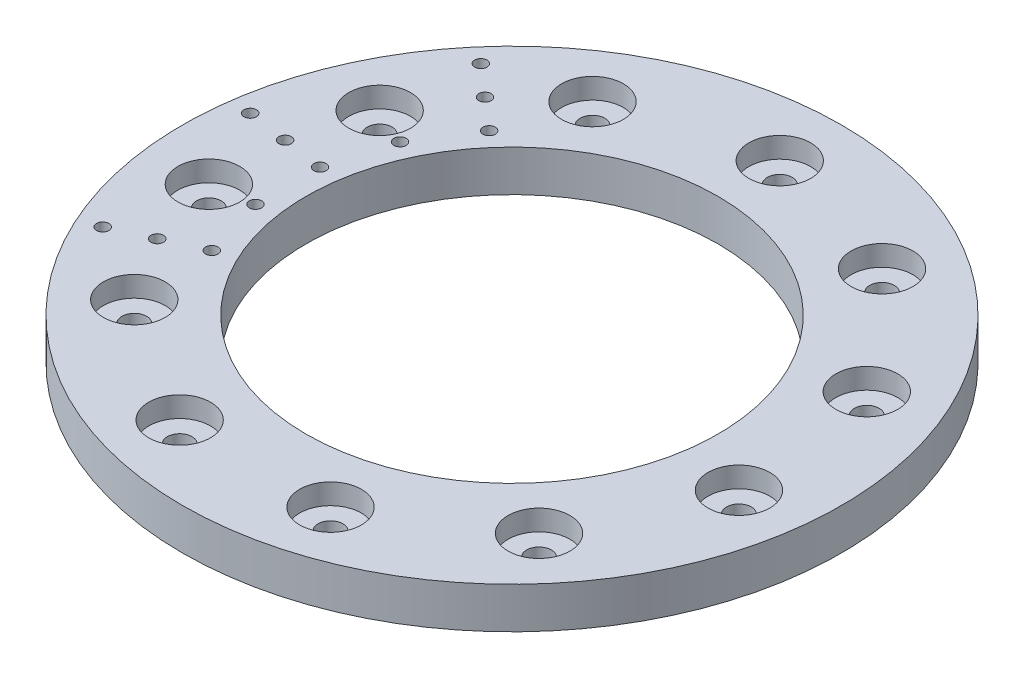
SolidWorks part; units mm, degrees
ref_plane "Front Plane" through (0, 0, 0) normal (0, 0, 1) x (1, 0, 0)
ref_plane "Top Plane" through (0, 0, 0) normal (0, 1, 0) x (1, 0, 0)
ref_plane "Right Plane" through (0, 0, 0) normal (1, 0, 0) x (0, 0, -1)
sketch "Sketch1" plane through (0, 0, 0) normal (0, 1, 0) x (1, 0, 0)
  circle A0 centre (0, 0) radius 80
  dimension "D1" = 160
extrude "Boss-Extrude1" add sketch "Sketch1" along normal blind 10
sketch "Sketch3" plane through (0, 10, 0) normal (0, 1, 0) x (1, 0, 0)
  circle A0 centre (0, 0) radius 65 construction
  circle A1 centre (0, 65) radius 3
  circle A2 centre (35.1417, 54.6815) radius 3
  circle A3 centre (59.1261, 27.002) radius 3
  circle A4 centre (64.3384, -9.2505) radius 3
  circle A5 centre (49.1237, -42.5659) radius 3
  circle A6 centre (18.3126, -62.367) radius 3
  circle A7 centre (-18.3126, -62.367) radius 3
  circle A8 centre (-49.1237, -42.5659) radius 3
  circle A9 centre (-64.3384, -9.2505) radius 3
  circle A10 centre (-59.1261, 27.002) radius 3
  circle A11 centre (-35.1417, 54.6815) radius 3
  point P27 (0, 0)
  dimension "D1" = 130
  dimension "D2" = 6
  dimension "D3" = 11
extrude "Cut-Extrude1" cut sketch "Sketch3" against normal blind 10
sketch "Sketch4" plane through (0, 10, 0) normal (0, 1, 0) x (1, 0, 0)
  circle A0 centre (0, 65) radius 7.5
  circle A1 centre (35.1417, 54.6815) radius 7.5
  circle A2 centre (59.1261, 27.002) radius 7.5
  circle A3 centre (64.3384, -9.2505) radius 7.5
  circle A4 centre (49.1237, -42.5659) radius 7.5
  circle A5 centre (18.3126, -62.367) radius 7.5
  circle A6 centre (-18.3126, -62.367) radius 7.5
  circle A7 centre (-49.1237, -42.5659) radius 7.5
  circle A8 centre (-64.3384, -9.2505) radius 7.5
  circle A9 centre (-59.1261, 27.002) radius 7.5
  circle A10 centre (-35.1417, 54.6815) radius 7.5
  point P25 (0, 0)
  dimension "D1" = 15
  dimension "D2" = 11
extrude "Cut-Extrude2" cut sketch "Sketch4" against normal blind 5
sketch "Sketch5" plane through (0, 10, 0) normal (0, 1, 0) x (1, 0, 0)
  circle A0 centre (0, 0) radius 50
  dimension "D1" = 100
extrude "Cut-Extrude3" cut sketch "Sketch5" against normal blind 21
sketch "Sketch6" plane through (0, 10, 0) normal (0, 1, 0) x (1, 0, 0)
  line L0 (0, 0) -> (-59.1261, 27.002) construction
  line L1 (-35.1417, 54.6815) -> (-59.1261, 27.002) construction
  line L2 (-59.1261, 27.002) -> (-64.3384, -9.2505) construction
  line L3 (-64.3384, -9.2505) -> (0, 0) construction
  line L4 (0, 0) -> (-35.1417, 54.6815) construction
  line L5 (0, 0) -> (-49.1237, -42.5659) construction
  line L6 (-64.3384, -9.2505) -> (-49.1237, -42.5659) construction
  line L7 (0, 0) -> (-59.1261, -27.002) construction
  line L8 (0, 0) -> (-64.3384, 9.2505) construction
  line L9 (0, 0) -> (-49.1237, 42.5659) construction
  line L10 (-49.1237, 42.5659) -> (-60.46, 52.3889) construction
  line L11 (0, 0) -> (-41.5662, 36.0173) construction
  line L12 (0, 0) -> (-54.4392, 7.8342) construction
  arc A1 (-35.1417, 54.6815) -> (-49.1237, -42.5659) centre (0, 0) ccw construction
  circle A3 centre (0, 0) radius 80 construction
  circle A4 centre (-56.6812, 49.1146) radius 1.5
  circle A5 centre (-49.1237, 42.5659) radius 1.5
  circle A6 centre (-41.5662, 36.0173) radius 1.5
  circle A7 centre (-54.4392, 7.8342) radius 1.5
  circle A8 centre (-64.3372, 9.2586) radius 1.5
  circle A9 centre (-74.2353, 10.683) radius 1.5
  circle A10 centre (-50.0356, -22.8351) radius 1.5
  circle A11 centre (-59.1329, -26.987) radius 1.5
  circle A12 centre (-68.2303, -31.1388) radius 1.5
  circle A13 centre (0, 0) radius 55 construction
  circle A14 centre (-50.0298, 22.8478) radius 1.5
  circle A15 centre (-54.4402, -7.8273) radius 1.5
  point P5 (0, 0)
  point P42 (-50.9776, 23.2807)
  point P43 (-50.0356, 22.8572)
  point P44 (-51.0338, -7.3376)
  point P45 (-54.4392, -7.8269)
  point P46 (-50.0356, 22.8351)
  point P47 (-54.4392, -7.8342)
  dimension "D1" = 10
  dimension "D4" = 3
  dimension "D3" = 3
  dimension "D2" = 10
  dimension "D5" = 32.72
extrude "Cut-Extrude4" cut sketch "Sketch6" against normal through all both and the other way through all
sketch "Sketch7" plane through (0, 10, 0) normal (0, 1, 0) x (1, 0, 0)
  line L0 (-54.4392, 7.8342) -> (-74.2353, 10.683)
ref_plane "Plane1" through (0, 0, 0) normal (0.1424, 0, -0.9898) x (-0.9898, 0, -0.1424)
